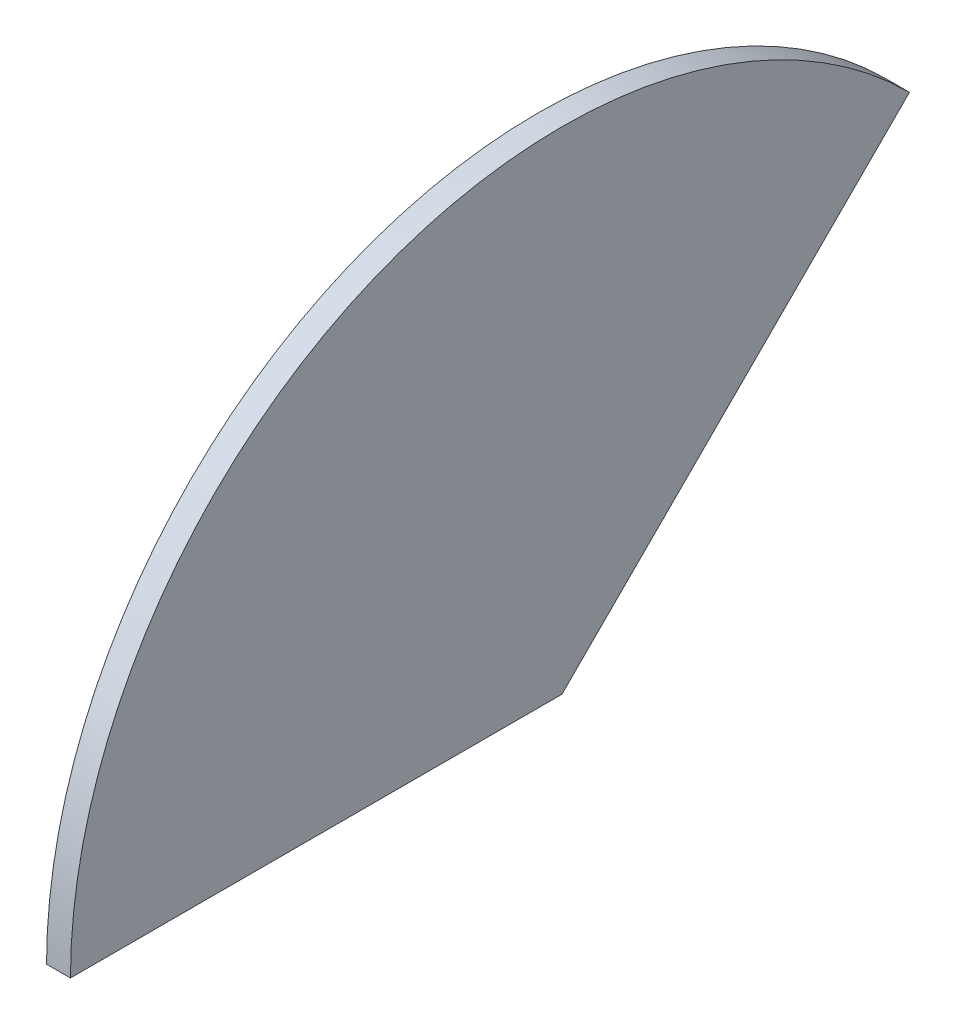
SolidWorks part; units mm, degrees
ref_plane "前视基准面" through (0, 0, 0) normal (0, 0, 1) x (1, 0, 0)
ref_plane "上视基准面" through (0, 0, 0) normal (0, 1, 0) x (1, 0, 0)
ref_plane "右视基准面" through (0, 0, 0) normal (1, 0, 0) x (0, 0, -1)
other "Configuration Table"
sketch "草图2" plane through (0, 0, 0) normal (1, 0, 0) x (0, 0, -1)
  line L1 (0, 0) -> (-185, 0)
  line L2 (0, 0) -> (130.8148, 130.8148)
  arc A0 (130.8148, 130.8148) -> (-185, 0) centre (0, 0) ccw
  dimension "D1" = 370
  dimension "D2" = 135
extrude "凸台-拉伸1" add sketch "草图2" along normal blind 9
